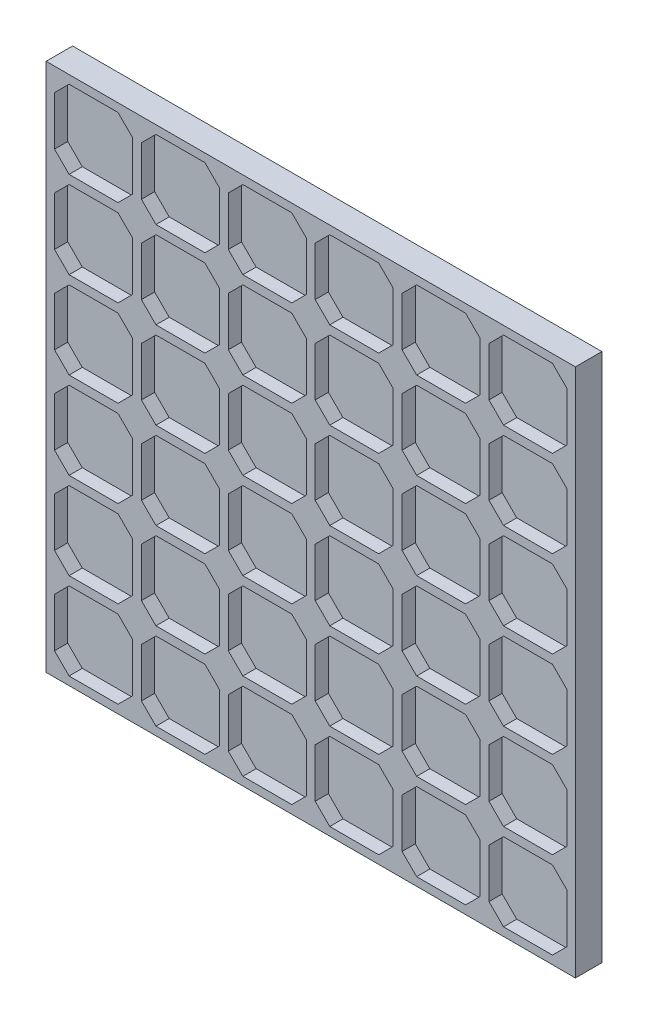
SolidWorks part; units mm, degrees
ref_plane "Ebene vorne" through (0, 0, 0) normal (0, 0, 1) x (1, 0, 0)
ref_plane "Ebene oben" through (0, 0, 0) normal (0, 1, 0) x (1, 0, 0)
ref_plane "Ebene rechts" through (0, 0, 0) normal (1, 0, 0) x (0, 0, -1)
sketch "Skizze1" plane through (0, 0, 0) normal (0, 0, 1) x (1, 0, 0)
  line L1 (0, 0) -> (240, 0)
  line L2 (0, 0) -> (0, 240)
  line L3 (0, 240) -> (240, 240)
  line L4 (240, 0) -> (240, 240)
  dimension "D1" = 240
  dimension "D2" = 240
extrude "Aufsatz-Linear austragen1" add sketch "Skizze1" along normal blind 6
sketch "Skizze2" plane through (0, 0, 6) normal (0, 0, 1) x (1, 0, 0)
  line L0 (0, 240) -> (0, 0) construction
  line L1 (2.5, 2.5) -> (237.5, 2.5)
  line L2 (2.5, 2.5) -> (2.5, 237.5)
  line L3 (2.5, 237.5) -> (237.5, 237.5)
  line L4 (237.5, 2.5) -> (237.5, 237.5)
  line L5 (0, 0) -> (240, 0) construction
  line L6 (240, 0) -> (240, 240) construction
  line L7 (240, 240) -> (0, 240) construction
  line L8 (0, 0) -> (240, 0)
  line L9 (240, 0) -> (240, 240)
  line L10 (240, 240) -> (0, 240)
  line L11 (0, 240) -> (0, 0)
  dimension "D1" = 235
  dimension "D2" = 235
  dimension "D3" = 2.5
  dimension "D4" = 2.5
extrude "Aufsatz-Linear austragen2" add sketch "Skizze2" along normal blind 6
sketch "Skizze3" plane through (0, 0, 6) normal (0, 0, 1) x (1, 0, 0)
  line L8 (30.5934, 198.8) -> (41.2, 209.4066)
  line L19 (240, 240) -> (0, 240) construction
  line L20 (0, 240) -> (0, 0) construction
  line L21 (240, 0) -> (240, 240) construction
  line L22 (0, 0) -> (240, 0) construction
  line L23 (240, 240) -> (0, 240)
  line L24 (0, 240) -> (0, 0)
  line L25 (30.5934, 198.8) -> (41.2, 188.1934)
  line L26 (41.2, 209.4066) -> (51.8066, 198.8)
  line L27 (41.2, 188.1934) -> (51.8066, 198.8)
  line L28 (0, 240) -> (0, 0) construction
  line L29 (41.2, 256.5118) -> (41.2, -31.9536) construction
  line L30 (-27.1037, 238.2) -> (265.7832, 238.2) construction
  line L31 (238.2, 246.684) -> (238.2, -31.9536) construction
  line L32 (80.6, 256.5118) -> (80.6, -31.9536) construction
  line L33 (120, 256.5118) -> (120, -31.9536) construction
  line L34 (159.4, 256.5118) -> (159.4, -31.9536) construction
  line L35 (198.8, 256.5118) -> (198.8, -31.9536) construction
  line L36 (-27.1037, 198.8) -> (265.7832, 198.8) construction
  line L37 (240, 0) -> (240, 240) construction
  line L38 (-27.1037, 159.4) -> (265.7832, 159.4) construction
  line L39 (-27.1037, 120) -> (265.7832, 120) construction
  line L40 (-27.1037, 80.6) -> (265.7832, 80.6) construction
  line L41 (-27.1037, 41.2) -> (265.7832, 41.2) construction
  line L42 (69.9934, 198.8) -> (80.6, 209.4066)
  line L43 (69.9934, 198.8) -> (80.6, 188.1934)
  line L44 (80.6, 209.4066) -> (91.2066, 198.8)
  line L45 (80.6, 188.1934) -> (91.2066, 198.8)
  line L46 (1.8, 256.5118) -> (1.8, -31.9536) construction
  line L47 (240, 240) -> (0, 240) construction
  line L49 (12.4066, 198.8) -> (1.8, 188.1934)
  line L50 (170.0066, 198.8) -> (159.4, 188.1934)
  line L51 (159.4, 188.1934) -> (148.7934, 198.8)
  line L52 (159.4, 209.4066) -> (148.7934, 198.8)
  line L53 (170.0066, 198.8) -> (159.4, 209.4066)
  line L54 (227.5934, 198.8) -> (238.2, 188.1934)
  line L57 (227.5934, 198.8) -> (238.2, 209.4066)
  line L58 (12.4066, 198.8) -> (1.8, 209.4066)
  line L60 (130.6066, 198.8) -> (120, 188.1934)
  line L61 (120, 188.1934) -> (109.3934, 198.8)
  line L62 (120, 209.4066) -> (109.3934, 198.8)
  line L63 (130.6066, 198.8) -> (120, 209.4066)
  line L64 (188.1934, 198.8) -> (198.8, 188.1934)
  line L65 (198.8, 188.1934) -> (209.4066, 198.8)
  line L66 (198.8, 209.4066) -> (209.4066, 198.8)
  line L67 (188.1934, 198.8) -> (198.8, 209.4066)
  line L68 (227.5934, 120) -> (238.2, 130.6066)
  line L69 (227.5934, 120) -> (238.2, 109.3934)
  line L70 (188.1934, 120) -> (198.8, 130.6066)
  line L71 (198.8, 130.6066) -> (209.4066, 120)
  line L72 (198.8, 109.3934) -> (209.4066, 120)
  line L73 (188.1934, 120) -> (198.8, 109.3934)
  line L74 (159.4, 130.6066) -> (148.7934, 120)
  line L75 (170.0066, 120) -> (159.4, 130.6066)
  line L76 (170.0066, 120) -> (159.4, 109.3934)
  line L77 (159.4, 109.3934) -> (148.7934, 120)
  line L78 (120, 130.6066) -> (109.3934, 120)
  line L79 (130.6066, 120) -> (120, 130.6066)
  line L80 (130.6066, 120) -> (120, 109.3934)
  line L81 (120, 109.3934) -> (109.3934, 120)
  line L82 (69.9934, 120) -> (80.6, 130.6066)
  line L83 (80.6, 130.6066) -> (91.2066, 120)
  line L84 (80.6, 109.3934) -> (91.2066, 120)
  line L85 (69.9934, 120) -> (80.6, 109.3934)
  line L86 (41.2, 109.3934) -> (51.8066, 120)
  line L87 (41.2, 130.6066) -> (51.8066, 120)
  line L88 (30.5934, 120) -> (41.2, 130.6066)
  line L89 (30.5934, 120) -> (41.2, 109.3934)
  line L90 (12.4066, 120) -> (1.8, 130.6066)
  line L91 (12.4066, 120) -> (1.8, 109.3934)
  line L92 (227.5934, 41.2) -> (238.2, 51.8066)
  line L93 (227.5934, 41.2) -> (238.2, 30.5934)
  line L94 (188.1934, 41.2) -> (198.8, 51.8066)
  line L95 (198.8, 51.8066) -> (209.4066, 41.2)
  line L96 (198.8, 30.5934) -> (209.4066, 41.2)
  line L97 (188.1934, 41.2) -> (198.8, 30.5934)
  line L98 (170.0066, 41.2) -> (159.4, 51.8066)
  line L99 (170.0066, 41.2) -> (159.4, 30.5934)
  line L100 (159.4, 30.5934) -> (148.7934, 41.2)
  line L101 (159.4, 51.8066) -> (148.7934, 41.2)
  line L102 (120, 51.8066) -> (109.3934, 41.2)
  line L103 (130.6066, 41.2) -> (120, 51.8066)
  line L104 (130.6066, 41.2) -> (120, 30.5934)
  line L105 (120, 30.5934) -> (109.3934, 41.2)
  line L106 (12.4066, 41.2) -> (1.8, 51.8066)
  line L107 (12.4066, 41.2) -> (1.8, 30.5934)
  line L108 (30.5934, 41.2) -> (41.2, 51.8066)
  line L109 (30.5934, 41.2) -> (41.2, 30.5934)
  line L110 (41.2, 30.5934) -> (51.8066, 41.2)
  line L111 (41.2, 51.8066) -> (51.8066, 41.2)
  line L112 (80.6, 51.8066) -> (91.2066, 41.2)
  line L113 (69.9934, 41.2) -> (80.6, 51.8066)
  line L114 (69.9934, 41.2) -> (80.6, 30.5934)
  line L115 (80.6, 30.5934) -> (91.2066, 41.2)
  line L116 (30.5934, 159.4) -> (41.2, 170.0066)
  line L117 (30.5934, 159.4) -> (41.2, 148.7934)
  line L118 (41.2, 170.0066) -> (51.8066, 159.4)
  line L119 (41.2, 148.7934) -> (51.8066, 159.4)
  line L120 (69.9934, 159.4) -> (80.6, 170.0066)
  line L121 (69.9934, 159.4) -> (80.6, 148.7934)
  line L122 (80.6, 170.0066) -> (91.2066, 159.4)
  line L123 (80.6, 148.7934) -> (91.2066, 159.4)
  line L126 (12.4066, 159.4) -> (1.8, 148.7934)
  line L127 (12.4066, 159.4) -> (1.8, 170.0066)
  line L128 (170.0066, 159.4) -> (159.4, 148.7934)
  line L129 (159.4, 148.7934) -> (148.7934, 159.4)
  line L130 (159.4, 170.0066) -> (148.7934, 159.4)
  line L131 (170.0066, 159.4) -> (159.4, 170.0066)
  line L132 (209.4066, 159.4) -> (198.8, 170.0066)
  line L133 (209.4066, 159.4) -> (198.8, 148.7934)
  line L134 (198.8, 148.7934) -> (188.1934, 159.4)
  line L135 (198.8, 170.0066) -> (188.1934, 159.4)
  line L136 (120, 148.7934) -> (130.6066, 159.4)
  line L137 (109.3934, 159.4) -> (120, 148.7934)
  line L138 (109.3934, 159.4) -> (120, 170.0066)
  line L139 (120, 170.0066) -> (130.6066, 159.4)
  line L140 (227.5934, 159.4) -> (238.2, 148.7934)
  line L143 (227.5934, 159.4) -> (238.2, 170.0066)
  line L144 (227.5934, 80.6) -> (238.2, 91.2066)
  line L145 (227.5934, 80.6) -> (238.2, 69.9934)
  line L146 (198.8, 91.2066) -> (188.1934, 80.6)
  line L147 (209.4066, 80.6) -> (198.8, 91.2066)
  line L148 (209.4066, 80.6) -> (198.8, 69.9934)
  line L149 (198.8, 69.9934) -> (188.1934, 80.6)
  line L150 (159.4, 91.2066) -> (148.7934, 80.6)
  line L151 (170.0066, 80.6) -> (159.4, 91.2066)
  line L152 (170.0066, 80.6) -> (159.4, 69.9934)
  line L153 (159.4, 69.9934) -> (148.7934, 80.6)
  line L154 (109.3934, 80.6) -> (120, 91.2066)
  line L155 (120, 91.2066) -> (130.6066, 80.6)
  line L156 (120, 69.9934) -> (130.6066, 80.6)
  line L157 (109.3934, 80.6) -> (120, 69.9934)
  line L158 (80.6, 69.9934) -> (91.2066, 80.6)
  line L159 (80.6, 91.2066) -> (91.2066, 80.6)
  line L160 (69.9934, 80.6) -> (80.6, 91.2066)
  line L161 (69.9934, 80.6) -> (80.6, 69.9934)
  line L162 (12.4066, 80.6) -> (1.8, 91.2066)
  line L163 (12.4066, 80.6) -> (1.8, 69.9934)
  line L164 (41.2, 69.9934) -> (51.8066, 80.6)
  line L165 (30.5934, 80.6) -> (41.2, 69.9934)
  line L166 (30.5934, 80.6) -> (41.2, 91.2066)
  line L167 (41.2, 91.2066) -> (51.8066, 80.6)
  line L168 (227.5934, 238.2) -> (238.2, 227.5934)
  line L169 (209.4066, 238.2) -> (198.8, 227.5934)
  line L170 (198.8, 227.5934) -> (188.1934, 238.2)
  line L171 (170.0066, 238.2) -> (159.4, 227.5934)
  line L172 (159.4, 227.5934) -> (148.7934, 238.2)
  line L173 (120, 227.5934) -> (130.6066, 238.2)
  line L174 (109.3934, 238.2) -> (120, 227.5934)
  line L175 (80.6, 227.5934) -> (91.2066, 238.2)
  line L176 (69.9934, 238.2) -> (80.6, 227.5934)
  line L177 (41.2, 227.5934) -> (51.8066, 238.2)
  line L178 (30.5934, 238.2) -> (41.2, 227.5934)
  line L179 (12.4066, 238.2) -> (1.8, 227.5934)
  line L180 (-26.9298, 1.8) -> (265.9571, 1.8) construction
  line L181 (0, 0) -> (240, 0) construction
  line L182 (227.5934, 1.8) -> (238.2, 12.4066)
  line L183 (209.4066, 1.8) -> (198.8, 12.4066)
  line L184 (198.8, 12.4066) -> (188.1934, 1.8)
  line L185 (170.0066, 1.8) -> (159.4, 12.4066)
  line L186 (159.4, 12.4066) -> (148.7934, 1.8)
  line L187 (120, 12.4066) -> (130.6066, 1.8)
  line L188 (109.3934, 1.8) -> (120, 12.4066)
  line L189 (80.6, 12.4066) -> (91.2066, 1.8)
  line L190 (69.9934, 1.8) -> (80.6, 12.4066)
  line L191 (12.4066, 1.8) -> (1.8, 12.4066)
  line L192 (41.2, 12.4066) -> (51.8066, 1.8)
  line L193 (30.5934, 1.8) -> (41.2, 12.4066)
  line L194 (1.8, 227.5934) -> (1.8, 209.4066)
  line L195 (12.4066, 238.2) -> (30.5934, 238.2)
  line L196 (51.8066, 238.2) -> (69.9934, 238.2)
  line L197 (91.2066, 238.2) -> (109.3934, 238.2)
  line L198 (130.6066, 238.2) -> (148.7934, 238.2)
  line L199 (170.0066, 238.2) -> (188.1934, 238.2)
  line L200 (209.4066, 238.2) -> (227.5934, 238.2)
  line L201 (238.2, 227.5934) -> (238.2, 209.4066)
  line L202 (238.2, 188.1934) -> (238.2, 170.0066)
  line L203 (238.2, 148.7934) -> (238.2, 130.6066)
  line L204 (238.2, 109.3934) -> (238.2, 91.2066)
  line L205 (238.2, 69.9934) -> (238.2, 51.8066)
  line L206 (238.2, 30.5934) -> (238.2, 12.4066)
  line L207 (227.5934, 1.8) -> (209.4066, 1.8)
  line L208 (188.1934, 1.8) -> (170.0066, 1.8)
  line L209 (148.7934, 1.8) -> (130.6066, 1.8)
  line L210 (109.3934, 1.8) -> (91.2066, 1.8)
  line L211 (69.9934, 1.8) -> (51.8066, 1.8)
  line L212 (30.5934, 1.8) -> (12.4066, 1.8)
  line L213 (1.8, 12.4066) -> (1.8, 30.5934)
  line L214 (1.8, 109.3934) -> (1.8, 91.2066)
  line L215 (1.8, 69.9934) -> (1.8, 51.8066)
  line L216 (1.8, 130.6066) -> (1.8, 148.7934)
  line L217 (1.8, 170.0066) -> (1.8, 188.1934)
  line L218 (240, 0) -> (240, 240)
  line L219 (0, 0) -> (240, 0)
  point P8 (0, 0)
  point P96 (164.7033, 193.4967)
  point P97 (232.8967, 193.4967)
  point P109 (46.5033, 204.1033)
  point P110 (114.6967, 193.4967)
  point P122 (114.6967, 125.3033)
  point P131 (46.5033, 114.6967)
  point P139 (35.8967, 125.3033)
  point P140 (204.1033, 125.3033)
  point P147 (204.1033, 35.8967)
  point P162 (35.8967, 35.8967)
  point P179 (85.9033, 164.7033)
  point P180 (46.5033, 164.7033)
  point P187 (75.2967, 154.0967)
  point P188 (164.7033, 154.0967)
  point P192 (154.0967, 164.7033)
  point P204 (193.4967, 154.0967)
  point P209 (193.4967, 85.9033)
  point P247 (46.5033, 232.8967)
  dimension "D15" = 45
  dimension "D16" = 15
  dimension "D17" = 15
  dimension "D20" = 41.2
  dimension "D21" = 39.4
  dimension "D22" = 39.4
  dimension "D23" = 39.4
  dimension "D24" = 39.4
  dimension "D25" = 41.2
  dimension "D26" = 39.4
  dimension "D27" = 39.4
  dimension "D28" = 39.4
  dimension "D29" = 39.4
  dimension "D30" = 1.8
  dimension "D31" = 1.8
  dimension "D32" = 1.8
  dimension "D33" = 1.8
extrude "Aufsatz-Linear austragen5" add sketch "Skizze3" along normal blind 6
sketch "Skizze4" plane through (0, 0, 6) normal (0, 0, 1) x (1, 0, 0)
  line L0 (39.2, 3.8) -> (39.2, 39.2)
  line L3 (43.2, 3.8) -> (43.2, 39.2)
  line L4 (41.2, 227.5934) -> (41.2, 12.4066) construction
  line L5 (78.6, 3.8) -> (78.6, 39.2)
  line L6 (82.6, 3.8) -> (82.6, 39.2)
  line L7 (80.6, 227.5934) -> (80.6, 12.4066) construction
  line L8 (120, 227.5934) -> (120, 12.4066) construction
  line L9 (118, 3.8) -> (118, 39.2)
  line L10 (122, 3.8) -> (122, 39.2)
  line L11 (159.4, 227.5934) -> (159.4, 12.4066) construction
  line L12 (157.4, 3.8) -> (157.4, 39.2)
  line L13 (161.4, 3.8) -> (161.4, 39.2)
  line L14 (198.8, 227.5934) -> (198.8, 12.4066) construction
  line L15 (196.8, 3.8) -> (196.8, 39.2)
  line L16 (200.8, 3.8) -> (200.8, 39.2)
  line L17 (12.4066, 198.8) -> (227.5934, 198.8) construction
  line L18 (12.4066, 159.4) -> (227.5934, 159.4) construction
  line L19 (227.5934, 120) -> (12.4066, 120) construction
  line L20 (12.4066, 80.6) -> (227.5934, 80.6) construction
  line L21 (12.4066, 41.2) -> (227.5934, 41.2) construction
  line L22 (3.8, 200.8) -> (39.2, 200.8)
  line L25 (3.8, 196.8) -> (39.2, 196.8)
  line L26 (3.8, 161.4) -> (39.2, 161.4)
  line L27 (3.8, 157.4) -> (39.2, 157.4)
  line L28 (3.8, 122) -> (39.2, 122)
  line L29 (3.8, 118) -> (39.2, 118)
  line L30 (3.8, 82.6) -> (39.2, 82.6)
  line L31 (3.8, 78.6) -> (39.2, 78.6)
  line L32 (3.8, 43.2) -> (39.2, 43.2)
  line L33 (3.8, 39.2) -> (39.2, 39.2)
  line L54 (43.2, 200.8) -> (78.6, 200.8)
  line L55 (39.2, 200.8) -> (39.2, 236.2)
  line L56 (43.2, 200.8) -> (43.2, 236.2)
  line L57 (43.2, 196.8) -> (78.6, 196.8)
  line L58 (82.6, 200.8) -> (118, 200.8)
  line L59 (78.6, 200.8) -> (78.6, 236.2)
  line L60 (82.6, 196.8) -> (118, 196.8)
  line L61 (82.6, 200.8) -> (82.6, 236.2)
  line L62 (118, 200.8) -> (118, 236.2)
  line L63 (122, 200.8) -> (157.4, 200.8)
  line L64 (122, 200.8) -> (122, 236.2)
  line L65 (122, 196.8) -> (157.4, 196.8)
  line L66 (157.4, 200.8) -> (157.4, 236.2)
  line L67 (161.4, 200.8) -> (196.8, 200.8)
  line L68 (161.4, 200.8) -> (161.4, 236.2)
  line L69 (161.4, 196.8) -> (196.8, 196.8)
  line L70 (196.8, 200.8) -> (196.8, 236.2)
  line L71 (200.8, 200.8) -> (236.2, 200.8)
  line L72 (200.8, 200.8) -> (200.8, 236.2)
  line L73 (200.8, 196.8) -> (236.2, 196.8)
  line L74 (200.8, 161.4) -> (200.8, 196.8)
  line L75 (200.8, 161.4) -> (236.2, 161.4)
  line L76 (196.8, 161.4) -> (196.8, 196.8)
  line L77 (200.8, 157.4) -> (236.2, 157.4)
  line L78 (161.4, 157.4) -> (196.8, 157.4)
  line L79 (161.4, 161.4) -> (161.4, 196.8)
  line L80 (157.4, 161.4) -> (157.4, 196.8)
  line L81 (161.4, 161.4) -> (196.8, 161.4)
  line L82 (122, 161.4) -> (122, 196.8)
  line L83 (122, 161.4) -> (157.4, 161.4)
  line L84 (118, 161.4) -> (118, 196.8)
  line L85 (122, 157.4) -> (157.4, 157.4)
  line L86 (82.6, 161.4) -> (82.6, 196.8)
  line L87 (82.6, 161.4) -> (118, 161.4)
  line L88 (78.6, 161.4) -> (78.6, 196.8)
  line L89 (82.6, 157.4) -> (118, 157.4)
  line L90 (43.2, 161.4) -> (43.2, 196.8)
  line L91 (43.2, 161.4) -> (78.6, 161.4)
  line L92 (39.2, 161.4) -> (39.2, 196.8)
  line L93 (43.2, 157.4) -> (78.6, 157.4)
  line L94 (39.2, 122) -> (39.2, 157.4)
  line L95 (43.2, 122) -> (78.6, 122)
  line L96 (43.2, 118) -> (78.6, 118)
  line L97 (43.2, 122) -> (43.2, 157.4)
  line L98 (78.6, 122) -> (78.6, 157.4)
  line L99 (82.6, 122) -> (118, 122)
  line L100 (82.6, 122) -> (82.6, 157.4)
  line L101 (82.6, 118) -> (118, 118)
  line L102 (118, 122) -> (118, 157.4)
  line L103 (122, 122) -> (157.4, 122)
  line L104 (122, 122) -> (122, 157.4)
  line L105 (122, 118) -> (157.4, 118)
  line L106 (157.4, 122) -> (157.4, 157.4)
  line L107 (161.4, 122) -> (196.8, 122)
  line L108 (161.4, 122) -> (161.4, 157.4)
  line L109 (161.4, 118) -> (196.8, 118)
  line L110 (196.8, 122) -> (196.8, 157.4)
  line L111 (200.8, 122) -> (236.2, 122)
  line L112 (200.8, 122) -> (200.8, 157.4)
  line L113 (200.8, 118) -> (236.2, 118)
  line L114 (196.8, 82.6) -> (196.8, 118)
  line L115 (200.8, 82.6) -> (236.2, 82.6)
  line L116 (200.8, 82.6) -> (200.8, 118)
  line L117 (200.8, 78.6) -> (236.2, 78.6)
  line L118 (161.4, 78.6) -> (196.8, 78.6)
  line L119 (161.4, 82.6) -> (161.4, 118)
  line L120 (161.4, 82.6) -> (196.8, 82.6)
  line L121 (157.4, 82.6) -> (157.4, 118)
  line L122 (118, 82.6) -> (118, 118)
  line L123 (122, 82.6) -> (157.4, 82.6)
  line L124 (122, 78.6) -> (157.4, 78.6)
  line L125 (122, 82.6) -> (122, 118)
  line L126 (82.6, 82.6) -> (82.6, 118)
  line L127 (82.6, 82.6) -> (118, 82.6)
  line L128 (78.6, 82.6) -> (78.6, 118)
  line L129 (82.6, 78.6) -> (118, 78.6)
  line L130 (39.2, 82.6) -> (39.2, 118)
  line L131 (43.2, 82.6) -> (78.6, 82.6)
  line L132 (43.2, 82.6) -> (43.2, 118)
  line L133 (43.2, 78.6) -> (78.6, 78.6)
  line L134 (39.2, 43.2) -> (39.2, 78.6)
  line L135 (43.2, 43.2) -> (78.6, 43.2)
  line L136 (43.2, 43.2) -> (43.2, 78.6)
  line L137 (43.2, 39.2) -> (78.6, 39.2)
  line L138 (78.6, 43.2) -> (78.6, 78.6)
  line L139 (82.6, 43.2) -> (118, 43.2)
  line L140 (82.6, 43.2) -> (82.6, 78.6)
  line L141 (82.6, 39.2) -> (118, 39.2)
  line L142 (118, 43.2) -> (118, 78.6)
  line L143 (122, 43.2) -> (157.4, 43.2)
  line L144 (122, 43.2) -> (122, 78.6)
  line L145 (122, 39.2) -> (157.4, 39.2)
  line L146 (157.4, 43.2) -> (157.4, 78.6)
  line L147 (161.4, 43.2) -> (196.8, 43.2)
  line L148 (161.4, 43.2) -> (161.4, 78.6)
  line L149 (161.4, 39.2) -> (196.8, 39.2)
  line L150 (196.8, 43.2) -> (196.8, 78.6)
  line L151 (200.8, 43.2) -> (236.2, 43.2)
  line L152 (200.8, 43.2) -> (200.8, 78.6)
  line L153 (200.8, 39.2) -> (236.2, 39.2)
  line L154 (2.5, 228.2934) -> (2.5, 208.7066) construction
  line L155 (3.8, 161.4) -> (3.8, 196.8)
  line L160 (3.8, 3.8) -> (39.2, 3.8)
  line L161 (3.8, 3.8) -> (3.8, 39.2)
  line L162 (3.8, 236.2) -> (39.2, 236.2)
  line L163 (236.2, 3.8) -> (236.2, 39.2)
  line L164 (31.2934, 237.5) -> (11.7066, 237.5) construction
  line L165 (237.5, 208.7066) -> (237.5, 228.2934) construction
  line L166 (3.8, 43.2) -> (3.8, 78.6)
  line L167 (3.8, 82.6) -> (3.8, 118)
  line L168 (3.8, 122) -> (3.8, 157.4)
  line L169 (3.8, 200.8) -> (3.8, 236.2)
  line L170 (43.2, 236.2) -> (78.6, 236.2)
  line L171 (82.6, 236.2) -> (118, 236.2)
  line L172 (122, 236.2) -> (157.4, 236.2)
  line L173 (161.4, 236.2) -> (196.8, 236.2)
  line L174 (200.8, 236.2) -> (236.2, 236.2)
  line L175 (236.2, 200.8) -> (236.2, 236.2)
  line L176 (236.2, 161.4) -> (236.2, 196.8)
  line L177 (236.2, 122) -> (236.2, 157.4)
  line L178 (236.2, 82.6) -> (236.2, 118)
  line L179 (236.2, 43.2) -> (236.2, 78.6)
  line L180 (200.8, 3.8) -> (236.2, 3.8)
  line L181 (161.4, 3.8) -> (196.8, 3.8)
  line L182 (122, 3.8) -> (157.4, 3.8)
  line L183 (82.6, 3.8) -> (118, 3.8)
  line L184 (43.2, 3.8) -> (78.6, 3.8)
  line L185 (11.7066, 2.5) -> (31.2934, 2.5) construction
  line L188 (0, 0) -> (240, 0)
  line L189 (0, 0) -> (0, 240)
  line L190 (0, 240) -> (240, 240)
  line L191 (240, 0) -> (240, 240)
  dimension "D1" = 4
  dimension "D2" = 4
  dimension "D3" = 4
  dimension "D4" = 4
  dimension "D5" = 4
  dimension "D6" = 4
  dimension "D7" = 4
  dimension "D8" = 4
  dimension "D9" = 4
  dimension "D10" = 4
  dimension "D11" = 1.3
  dimension "D12" = 1.3
  dimension "D13" = 1.3
  dimension "D14" = 1.3
extrude "Aufsatz-Linear austragen6" add sketch "Skizze4" along normal blind 6
